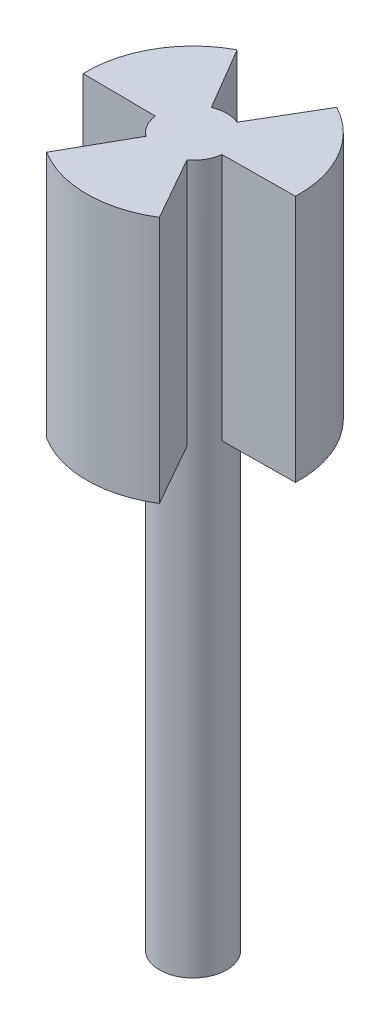
SolidWorks part; units mm, degrees
ref_plane "Front Plane" through (0, 0, 0) normal (0, 0, 1) x (1, 0, 0)
ref_plane "Top Plane" through (0, 0, 0) normal (0, 1, 0) x (1, 0, 0)
ref_plane "Right Plane" through (0, 0, 0) normal (1, 0, 0) x (0, 0, -1)
sketch "Sketch1" plane through (0, 0, 0) normal (0, 1, 0) x (1, 0, 0)
  circle A0 centre (0, 0) radius 9.5
  dimension "D1" = 19
extrude "Boss-Extrude1" add sketch "Sketch1" along normal blind 200
sketch "Sketch2" plane through (0, 200, 0) normal (0, 1, 0) x (1, 0, 0)
  circle A0 centre (0, 0) radius 30
  circle A1 centre (0, 0) radius 9.5 construction
  circle A2 centre (0, 0) radius 9.5
  dimension "D1" = 60
extrude "Boss-Extrude2" add sketch "Sketch2" against normal blind 70
sketch "Sketch3" plane through (0, 130, 0) normal (0, -1, 0) x (1, 0, 0)
  line L0 (0, -9.5) -> (0, -37.9385) construction
  line L1 (20.8054, -37.9385) -> (-20.8054, -37.9385)
  line L2 (-20.8054, -37.9385) -> (-3.6215, -8.7826)
  line L3 (20.8054, -37.9385) -> (3.6215, -8.7826)
  circle A0 centre (0, 0) radius 9.5 construction
  circle A1 centre (0, 0) radius 9.5 construction
  arc A2 (-3.6215, -8.7826) -> (3.6215, -8.7826) centre (0, 0) ccw
extrude "Cut-Extrude1" cut sketch "Sketch3" against normal through all
pattern_circular "CirPattern1" count 3 over 360 about axis through (0, 0, 0) along (0, 1, 0) of "Cut-Extrude1"
